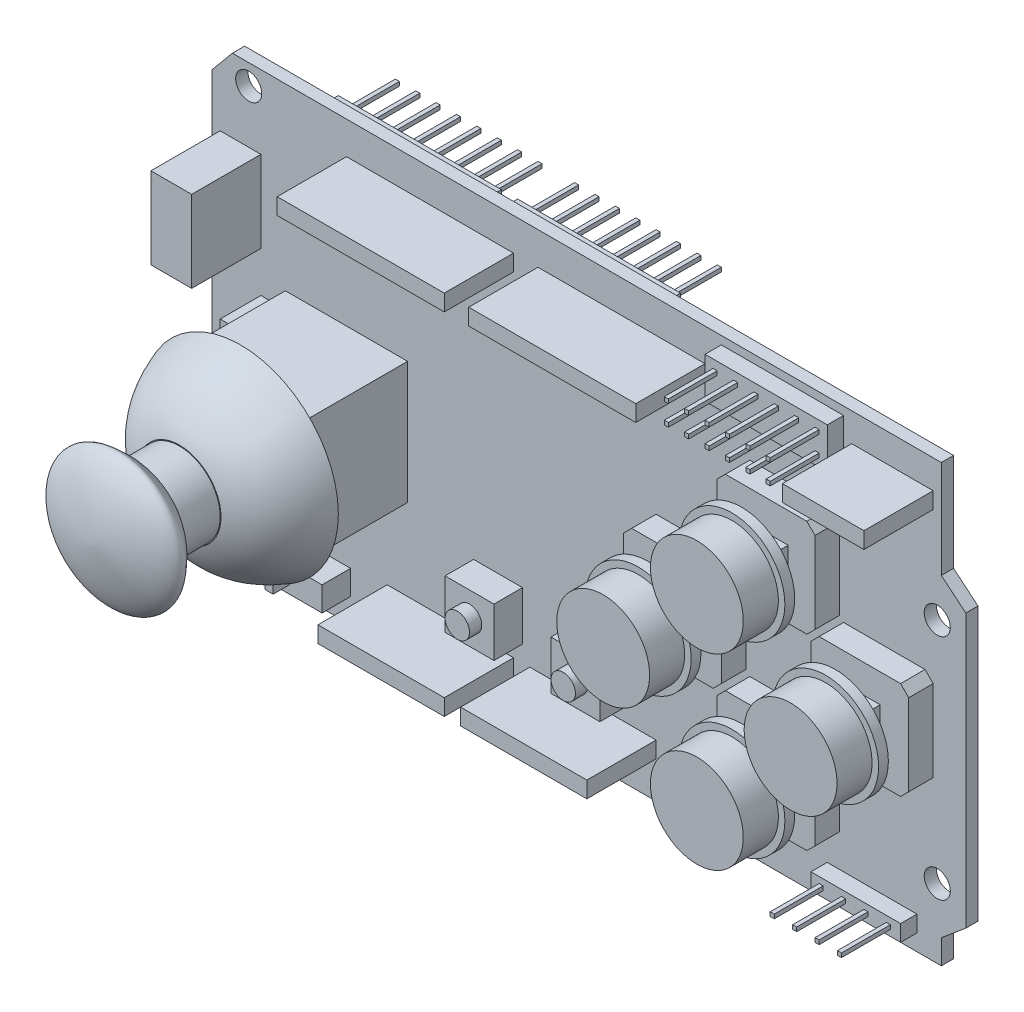
SolidWorks part; units mm, degrees
ref_plane "前视基准面" through (0, 0, 0) normal (0, 0, 1) x (1, 0, 0)
ref_plane "上视基准面" through (0, 0, 0) normal (0, 1, 0) x (1, 0, 0)
ref_plane "右视基准面" through (0, 0, 0) normal (1, 0, 0) x (0, 0, -1)
sketch "草图2" plane through (0, 0, 0) normal (0, 0, 1) x (1, 0, 0)
  line L0 (0, 0) -> (86, 0)
  line L1 (86, 0) -> (86, 3)
  line L2 (86, 3) -> (89, 5.5)
  line L3 (89, 5.5) -> (89, 39)
  line L4 (89, 39) -> (86, 41.5)
  line L5 (86, 41.5) -> (86, 53.5)
  line L6 (0, 0) -> (0, 14)
  line L7 (0, 14) -> (-3.5, 17.5)
  line L8 (-3.5, 17.5) -> (-3.5, 50.5)
  line L9 (-3.5, 50.5) -> (-1, 53.5)
  line L10 (-1, 53.5) -> (86, 53.5)
  dimension "D1" = 86
  dimension "D2" = 3
  dimension "D3" = 2.5
  dimension "D4" = 3
  dimension "D5" = 33.5
  dimension "D6" = 3
  dimension "D7" = 2.5
  dimension "D8" = 53.5
  dimension "D9" = 14
  dimension "D10" = 3.5
  dimension "D11" = 3.5
  dimension "D12" = 33
  dimension "D13" = 2.5
extrude "凸台-拉伸1" add sketch "草图2" along normal blind 1.5
sketch "草图3" plane through (0, 0, 1.5) normal (0, 0, 1) x (1, 0, 0)
  line L0 (89, 5.5) -> (89, 39) construction
  line L1 (86, 53.5) -> (-1, 53.5) construction
  line L2 (-3.5, 50.5) -> (-3.5, 17.5) construction
  circle A0 centre (85.5, 36.5) radius 1.6
  circle A1 centre (85.5, 8.5) radius 1.6
  circle A2 centre (1, 51) radius 1.6
  dimension "D1" = 3.5
  dimension "D2" = 2.5
  dimension "D3" = 28
  dimension "D4" = 2.5
  dimension "D5" = 4.5
extrude "切除-拉伸1" cut sketch "草图3" against normal through all
sketch "草图4" plane through (0, 0, 1.5) normal (0, 0, 1) x (1, 0, 0)
  line L0 (89, 5.5) -> (89, 39) construction
  line L1 (73, 30.5) -> (85, 30.5)
  line L2 (73, 30.5) -> (73, 18.5)
  line L3 (73, 18.5) -> (85, 18.5)
  line L4 (85, 30.5) -> (85, 18.5)
  line L5 (73, 30.5) -> (85, 18.5) construction
  line L6 (73, 18.5) -> (85, 30.5) construction
  circle A0 centre (85.5, 36.5) radius 1.6 construction
  point P0 (79, 24.5)
  dimension "D1" = 12
  dimension "D2" = 12
  dimension "D3" = 4
  dimension "D4" = 6
extrude "凸台-拉伸2" add sketch "草图4" along normal blind 3
chamfer "倒角1" distance 1 angle 45 4 edges at (73, 30.5, 3) (73, 18.5, 3) (85, 18.5, 3) (85, 30.5, 3)
sketch "草图5" plane through (0, 0, 1.5) normal (0, 0, 1) x (1, 0, 0)
  line L0 (84, 30.5) -> (74, 30.5) construction
  line L1 (73, 29.5) -> (73, 19.5) construction
  line L2 (74, 18.5) -> (84, 18.5) construction
  point P0 (67.5, 36)
  point P5 (67.5, 13)
  point P8 (56, 24.5)
  point P11 (79, 24.5)
  dimension "D1" = 5.5
  dimension "D2" = 5.5
  dimension "D3" = 5.5
  dimension "D4" = 11.5
ref_plane "基准面4" through (67.5, 0, 0) normal (-1, 0, 0) x (0, 0, 1)
mirror "镜向1" about plane through (67.5, 0, 0) normal (-1, 0, 0) of "倒角1", "凸台-拉伸2"
sketch "草图6" plane through (0, 0, 1.5) normal (0, 0, 1) x (1, 0, 0)
  line L0 (72.5, 42) -> (73.5, 41)
  line L1 (72.5, 42) -> (62.5, 42)
  line L2 (73.5, 41) -> (73.5, 31)
  line L3 (72.5, 30) -> (62.5, 30)
  line L4 (61.5, 41) -> (61.5, 31)
  line L5 (73.5, 42) -> (61.5, 30) construction
  line L6 (73.5, 30) -> (61.5, 42) construction
  line L7 (72.5, 19) -> (62.5, 19)
  line L8 (73.5, 18) -> (73.5, 8)
  line L9 (72.5, 7) -> (62.5, 7)
  line L10 (61.5, 18) -> (61.5, 8)
  line L11 (73.5, 19) -> (61.5, 7) construction
  line L12 (73.5, 7) -> (61.5, 19) construction
  line L13 (73.5, 31) -> (72.5, 30)
  line L14 (62.5, 42) -> (61.5, 41)
  line L15 (62.5, 30) -> (61.5, 31)
  line L16 (73.5, 18) -> (72.5, 19)
  line L17 (73.5, 8) -> (72.5, 7)
  line L18 (62.5, 19) -> (61.5, 18)
  line L19 (62.5, 7) -> (61.5, 8)
  point P0 (67.5, 36)
  point P6 (67.5, 13)
  dimension "D1" = 12
  dimension "D2" = 12
  dimension "D3" = 12
  dimension "D4" = 12
extrude "凸台-拉伸4" add sketch "草图6" along normal blind 3
sketch "草图7" plane through (0, 0, 4.5) normal (0, 0, 1) x (1, 0, 0)
  line L0 (70.2067, 38.3082) -> (65.2067, 38.3082)
  line L1 (81.5, 27) -> (76.5, 27)
  line L2 (81.5, 27) -> (81.5, 22)
  line L3 (81.5, 22) -> (76.5, 22)
  line L4 (76.5, 27) -> (76.5, 22)
  line L5 (81.5, 27) -> (76.5, 22) construction
  line L6 (81.5, 22) -> (76.5, 27) construction
  line L7 (70.2067, 38.3082) -> (70.2067, 33.3082)
  line L8 (70.2067, 33.3082) -> (65.2067, 33.3082)
  line L9 (65.2067, 38.3082) -> (65.2067, 33.3082)
  line L10 (70.2067, 38.3082) -> (65.2067, 33.3082) construction
  line L11 (70.2067, 33.3082) -> (65.2067, 38.3082) construction
  line L12 (58.565, 27.0711) -> (53.565, 27.0711)
  line L13 (58.565, 27.0711) -> (58.565, 22.0711)
  line L14 (58.565, 22.0711) -> (53.565, 22.0711)
  line L15 (53.565, 27.0711) -> (53.565, 22.0711)
  line L16 (58.565, 27.0711) -> (53.565, 22.0711) construction
  line L17 (58.565, 22.0711) -> (53.565, 27.0711) construction
  line L18 (69.8471, 15.3845) -> (64.8471, 15.3845)
  line L19 (69.8471, 15.3845) -> (69.8471, 10.3845)
  line L20 (69.8471, 10.3845) -> (64.8471, 10.3845)
  line L21 (64.8471, 15.3845) -> (64.8471, 10.3845)
  line L22 (69.8471, 15.3845) -> (64.8471, 10.3845) construction
  line L23 (69.8471, 10.3845) -> (64.8471, 15.3845) construction
  point P0 (79, 24.5)
  point P6 (67.7067, 35.8082)
  point P11 (56.065, 24.5711)
  point P16 (67.3471, 12.8845)
  dimension "D1" = 5
  dimension "D2" = 5
  dimension "D3" = 5
  dimension "D4" = 5
  dimension "D5" = 5
  dimension "D6" = 5
  dimension "D7" = 5
  dimension "D8" = 5
extrude "凸台-拉伸5" add sketch "草图7" along normal blind 3
sketch "草图8" plane through (0, 0, 7.5) normal (0, 0, 1) x (1, 0, 0)
  circle A0 centre (67.5, 36) radius 6.5
  circle A1 centre (67.5, 13) radius 6.5
extrude "凸台-拉伸6" add sketch "草图8" along normal blind 1.2
sketch "草图9" plane through (0, 0, 8.7) normal (0, 0, 1) x (1, 0, 0)
  circle A0 centre (67.5, 36) radius 5.7
  circle A1 centre (67.5, 13) radius 5.7
extrude "凸台-拉伸7" add sketch "草图9" along normal blind 4.3
sketch "草图10" plane through (0, 0, 7.5) normal (0, 0, 1) x (1, 0, 0)
  circle A0 centre (56, 24.5) radius 6.5
  circle A1 centre (79, 24.5) radius 6.5
extrude "凸台-拉伸8" add sketch "草图10" along normal blind 1.2
sketch "草图11" plane through (0, 0, 8.7) normal (0, 0, 1) x (1, 0, 0)
  circle A0 centre (56, 24.5) radius 5.7
  circle A1 centre (79, 24.5) radius 5.7
extrude "凸台-拉伸9" add sketch "草图11" along normal blind 4.3
sketch "草图12" plane through (0, 0, 1.5) normal (0, 0, 1) x (1, 0, 0)
  line L0 (0, 0) -> (86, 0) construction
  line L2 (0, 29) -> (1.5, 29)
  line L3 (0, 29) -> (0, 19)
  line L4 (0, 19) -> (1.5, 19)
  line L6 (1.5, 29) -> (1.5436, 29)
  line L7 (1.5, 19) -> (1.5436, 19)
  line L8 (-3.5, 50.5) -> (-3.5, 17.5) construction
  arc A0 (1.5436, 19) -> (1.5436, 29) centre (13, 24) ccw
  point P9 (0, 24)
  dimension "D1" = 24
  dimension "D4" = 13
  dimension "D2" = 10
  dimension "D3" = 1.5
  dimension "D5" = 0
  dimension "D6" = 3.5
sketch "草图13" plane through (0, 0, 1.5) normal (0, 0, 1) x (1, 0, 0)
  line L0 (5.5, 29.5) -> (2.5, 29.5)
  line L1 (5.5, 16.5) -> (20.5, 16.5)
  line L2 (5.5, 16.5) -> (5.5, 18.5)
  line L3 (5.5, 31.5) -> (20.5, 31.5)
  line L4 (20.5, 16.5) -> (20.5, 31.5)
  line L5 (5.5, 29.5) -> (5.5, 31.5)
  line L10 (2.5, 18.5) -> (2.5, 29.5)
  line L12 (5.5, 18.5) -> (2.5, 18.5)
  point P0 (13, 24)
  point P6 (5.5, 24)
  dimension "D1" = 15
  dimension "D2" = 15
  dimension "D3" = 11
extrude "凸台-拉伸10" add sketch "草图13" along normal blind 13
sketch "草图15" plane through (0, 0, 14.5) normal (0, 0, 1) x (1, 0, 0)
  circle A0 centre (13, 24) radius 12
ref_plane "基准面5" through (0, 0, 22) normal (0, 0, 1) x (1, 0, 0)
sketch "草图16" plane through (0, 0, 22) normal (0, 0, 1) x (1, 0, 0)
  circle A0 centre (13, 24) radius 5.1
ref_plane "基准面6" through (0, 24, 0) normal (0, -1, 0) x (-1, 0, 0)
sketch "草图17" plane through (0, 24, 0) normal (0, -1, 0) x (-1, 0, 0)
  line L8 (-18.1, -22) -> (-7.9, -22) construction
  line L9 (-8.25, -22) -> (8.25, -22) construction
  line L10 (-25, -14.5) -> (-1, -14.5) construction
  line L11 (-18.1, -22) -> (-13, -22)
  line L12 (-13, -22) -> (-13, -14.5)
  line L13 (-13, -14.5) -> (-25, -14.5)
  spline S0 degree 2 poles (-18.1, -22) (-23.0643, -20.3891) (-25, -14.5) knots 0 0 0 1 1 1
extrude "凸台-拉伸11" add sketch "草图16" against normal blind 13 contours A0
revolve "旋转1" add sketch "草图17" angle 360 about L12
sketch "草图18" plane through (0, 18.5, 0) normal (0, -1, 0) x (1, 0, 0)
  line L0 (5.5, 14.5) -> (5.5, 1.5) construction
  line L1 (2.5, 14.5) -> (5.5, 14.5)
  line L2 (2.5, 14.5) -> (2.5, 6.5)
  line L3 (2.5, 6.5) -> (5.5, 6.5)
  line L4 (5.5, 14.5) -> (5.5, 6.5)
  dimension "D1" = 8
extrude "切除-拉伸2" cut sketch "草图18" against normal through all
sketch "草图19" plane through (0, 0, 22) normal (0, 0, 1) x (1, 0, 0)
  circle A0 centre (13, 24) radius 5
extrude "凸台-拉伸12" add sketch "草图19" along normal blind 5
sketch "草图20" plane through (0, 24, 0) normal (0, -1, 0) x (-1, 0, 0)
  line L0 (-13, -27) -> (-13, -33)
  line L1 (-18, -27) -> (-8, -27) construction
  line L2 (-18, -27) -> (-13, -27)
  spline S0 degree 3 poles (-13, -33) (-17.4258, -32.7506) (-22.378, -30.5813) (-20.7084, -28.8669) (-19.1499, -27.0475) (-18, -27) knots 0 0 0 0 0.726319 0.826319 1 1 1 1
  dimension "D1" = 6
revolve "旋转2" add sketch "草图20" angle 360 about L0
sketch "草图21" plane through (0, 0, 1.5) normal (0, 0, 1) x (1, 0, 0)
  line L0 (86, 41.5) -> (86, 53.5) construction
  line L1 (59, 52.5) -> (74, 52.5)
  line L2 (59, 52.5) -> (59, 47.5)
  line L3 (59, 47.5) -> (74, 47.5)
  line L4 (74, 52.5) -> (74, 47.5)
  line L5 (86, 53.5) -> (-1, 53.5) construction
  dimension "D1" = 15
  dimension "D2" = 5
  dimension "D3" = 12
  dimension "D4" = 1
extrude "凸台-拉伸13" add sketch "草图21" along normal blind 2
sketch "草图22" plane through (0, 0, 1.5) normal (0, 0, 1) x (1, 0, 0)
  line L0 (0, 0) -> (86, 0) construction
  line L1 (72, 2) -> (83, 2)
  line L2 (72, 2) -> (72, 4)
  line L3 (72, 4) -> (83, 4)
  line L4 (83, 2) -> (83, 4)
  line L5 (86, 0) -> (86, 3) construction
  dimension "D1" = 11
  dimension "D2" = 2
  dimension "D3" = 2
  dimension "D4" = 3
extrude "凸台-拉伸14" add sketch "草图22" along normal blind 2
sketch "草图23" plane through (0, 0, 3.5) normal (0, 0, 1) x (1, 0, 0)
  line L0 (72, 4) -> (72, 2) construction
  line L1 (73, 2.75) -> (73.5, 2.75)
  line L2 (73, 2.75) -> (73, 3.25)
  line L3 (73, 3.25) -> (73.5, 3.25)
  line L4 (73.5, 2.75) -> (73.5, 3.25)
  line L5 (83, 4) -> (72, 4) construction
  dimension "D1" = 0.5
  dimension "D2" = 0.5
  dimension "D3" = 1
  dimension "D4" = 0.75
extrude "凸台-拉伸15" add sketch "草图23" along normal blind 6
pattern_linear "阵列(线性)1" count 4 spacing 2.75 along (1, 0, 0) of "凸台-拉伸15"
sketch "草图24" plane through (0, 0, 3.5) normal (0, 0, 1) x (1, 0, 0)
  line L0 (59, 47.5) -> (74, 47.5) construction
  line L1 (73, 48.5) -> (72.5, 48.5)
  line L2 (73, 48.5) -> (73, 49)
  line L3 (73, 49) -> (72.5, 49)
  line L4 (72.5, 48.5) -> (72.5, 49)
  line L5 (74, 47.5) -> (74, 52.5) construction
  line L6 (74, 52.5) -> (59, 52.5) construction
  line L7 (73, 51) -> (72.5, 51)
  line L8 (73, 51) -> (73, 51.5)
  line L9 (73, 51.5) -> (72.5, 51.5)
  line L10 (72.5, 51) -> (72.5, 51.5)
  dimension "D1" = 0.5
  dimension "D2" = 0.5
  dimension "D3" = 1
  dimension "D4" = 1
  dimension "D5" = 0.5
  dimension "D6" = 1
extrude "凸台-拉伸16" add sketch "草图24" along normal blind 6
pattern_linear "阵列(线性)2" count 6 spacing 2.5 along (-1, 0, 0) of "凸台-拉伸16"
sketch "草图25" plane through (0, 0, 1.5) normal (0, 0, 1) x (1, 0, 0)
  line L0 (86, 53.5) -> (-1, 53.5) construction
  line L1 (85, 48) -> (75, 48)
  line L2 (85, 48) -> (85, 50)
  line L3 (85, 50) -> (75, 50)
  line L4 (75, 48) -> (75, 50)
  line L5 (74, 47.5) -> (74, 52.5) construction
  line L6 (59, 52.5) -> (59, 47.5) construction
  line L7 (57, 47.5) -> (36.5, 47.5)
  line L8 (57, 47.5) -> (57, 49.5)
  line L9 (57, 49.5) -> (36.5, 49.5)
  line L10 (36.5, 47.5) -> (36.5, 49.5)
  line L11 (33.5, 47.5) -> (13, 47.5)
  line L12 (33.5, 47.5) -> (33.5, 49.5)
  line L13 (33.5, 49.5) -> (13, 49.5)
  line L14 (13, 47.5) -> (13, 49.5)
  line L15 (-3.5, 50.5) -> (-3.5, 17.5) construction
  line L16 (2.5, 34.5) -> (-2.5, 34.5)
  line L17 (2.5, 34.5) -> (2.5, 44.5)
  line L18 (2.5, 44.5) -> (-2.5, 44.5)
  line L19 (-2.5, 34.5) -> (-2.5, 44.5)
  line L20 (0, 14) -> (0, 0) construction
  line L21 (51, 4.5) -> (35.5, 4.5)
  line L22 (51, 4.5) -> (51, 6.5)
  line L23 (51, 6.5) -> (35.5, 6.5)
  line L24 (35.5, 4.5) -> (35.5, 6.5)
  line L25 (33.5, 4.5) -> (18, 4.5)
  line L26 (33.5, 4.5) -> (33.5, 6.5)
  line L27 (33.5, 6.5) -> (18, 6.5)
  line L28 (18, 4.5) -> (18, 6.5)
  line L29 (0, 0) -> (86, 0) construction
  dimension "D1" = 10
  dimension "D2" = 2
  dimension "D3" = 3.5
  dimension "D4" = 1
  dimension "D5" = 20.5
  dimension "D6" = 20.5
  dimension "D7" = 2
  dimension "D8" = 2
  dimension "D9" = 2
  dimension "D10" = 4
  dimension "D11" = 3
  dimension "D12" = 4
  dimension "D13" = 10
  dimension "D14" = 5
  dimension "D15" = 1
  dimension "D16" = 9
  dimension "D17" = 15.5
  dimension "D18" = 15.5
  dimension "D19" = 2
  dimension "D20" = 2
  dimension "D21" = 18
  dimension "D22" = 4.5
  dimension "D23" = 4.5
  dimension "D24" = 2
extrude "凸台-拉伸17" add sketch "草图25" along normal blind 8.5
sketch "草图26" plane through (0, 0, 1.5) normal (0, 0, 1) x (1, 0, 0)
  line L0 (0, 14) -> (0, 0) construction
  line L1 (4.5, 6) -> (13.5, 6)
  line L2 (4.5, 6) -> (4.5, 3)
  line L3 (4.5, 3) -> (13.5, 3)
  line L4 (13.5, 6) -> (13.5, 3)
  line L5 (0, 0) -> (86, 0) construction
  dimension "D1" = 9
  dimension "D2" = 3
  dimension "D3" = 4.5
  dimension "D4" = 3
extrude "凸台-拉伸18" add sketch "草图26" along normal blind 3.5
sketch "草图27" plane through (0, 0, 5) normal (0, 0, 1) x (1, 0, 0)
  line L0 (4.5, 3) -> (13.5, 3) construction
  line L1 (8.5, 5) -> (9.5, 5)
  line L2 (8.5, 5) -> (8.5, 4)
  line L3 (8.5, 4) -> (9.5, 4)
  line L4 (9.5, 5) -> (9.5, 4)
  line L5 (4.5, 6) -> (4.5, 3) construction
  dimension "D1" = 1
  dimension "D2" = 1
  dimension "D3" = 1
  dimension "D4" = 4
extrude "凸台-拉伸19" add sketch "草图27" along normal blind 2
sketch "草图28" plane through (0, 0, 1.5) normal (0, 0, 1) x (1, 0, 0)
  line L0 (33.5, 4.5) -> (33.5, 6.5) construction
  line L1 (28.6, 14.5) -> (34.6, 14.5)
  line L2 (28.6, 14.5) -> (28.6, 8.5)
  line L3 (28.6, 8.5) -> (34.6, 8.5)
  line L4 (34.6, 14.5) -> (34.6, 8.5)
  line L5 (41.6, 14.5) -> (47.6, 14.5)
  line L6 (41.6, 14.5) -> (41.6, 8.5)
  line L7 (41.6, 8.5) -> (47.6, 8.5)
  line L8 (47.6, 14.5) -> (47.6, 8.5)
  line L9 (33.5, 6.5) -> (18, 6.5) construction
  line L10 (51, 6.5) -> (35.5, 6.5) construction
  point P10 (33.5, 5.5)
  dimension "D1" = 6
  dimension "D2" = 6
  dimension "D3" = 6
  dimension "D4" = 6
  dimension "D5" = 1.1
  dimension "D6" = 2
  dimension "D7" = 2
  dimension "D8" = 7
extrude "凸台-拉伸20" add sketch "草图28" along normal blind 3.5
sketch "草图29" plane through (0, 0, 5) normal (0, 0, 1) x (1, 0, 0)
  circle A0 centre (31.6, 11.5) radius 1.5
  circle A1 centre (44.6, 11.5) radius 1.5
extrude "凸台-拉伸21" add sketch "草图29" along normal blind 1.5
sketch "草图30" plane through (0, 0, 0) normal (0, 0, -1) x (-1, 0, 0)
  line L0 (0, 14) -> (0, 0) construction
  line L1 (-18, 2) -> (-33, 2)
  line L2 (-18, 2) -> (-18, 4)
  line L3 (-18, 4) -> (-33, 4)
  line L4 (-33, 2) -> (-33, 4)
  line L5 (-36, 2) -> (-51, 2)
  line L6 (-36, 2) -> (-36, 4)
  line L7 (-36, 4) -> (-51, 4)
  line L8 (-51, 2) -> (-51, 4)
  line L9 (0, 0) -> (-86, 0) construction
  line L10 (3.5, 50.5) -> (3.5, 17.5) construction
  line L11 (-8.5, 50) -> (-28.5, 50)
  line L12 (-8.5, 50) -> (-8.5, 52)
  line L13 (-8.5, 52) -> (-28.5, 52)
  line L14 (-28.5, 50) -> (-28.5, 52)
  line L15 (-30.5, 50) -> (-50.5, 50)
  line L16 (-30.5, 50) -> (-30.5, 52)
  line L17 (-30.5, 52) -> (-50.5, 52)
  line L18 (-50.5, 50) -> (-50.5, 52)
  line L19 (-86, 53.5) -> (1, 53.5) construction
  dimension "D1" = 15
  dimension "D2" = 15
  dimension "D3" = 2
  dimension "D4" = 2
  dimension "D5" = 18
  dimension "D6" = 2
  dimension "D7" = 2
  dimension "D8" = 3
  dimension "D9" = 20
  dimension "D10" = 20
  dimension "D11" = 2
  dimension "D12" = 2
  dimension "D13" = 2
  dimension "D14" = 12
  dimension "D15" = 1.5
extrude "凸台-拉伸22" add sketch "草图30" along normal blind 2
sketch "草图31" plane through (0, 0, -2) normal (0, 0, -1) x (-1, 0, 0)
  line L0 (-33, 2) -> (-18, 2) construction
  line L1 (-19, 2.75) -> (-19.5, 2.75)
  line L2 (-19, 2.75) -> (-19, 3.25)
  line L3 (-19, 3.25) -> (-19.5, 3.25)
  line L4 (-19.5, 2.75) -> (-19.5, 3.25)
  line L5 (-37, 2.75) -> (-37.5, 2.75)
  line L6 (-37, 2.75) -> (-37, 3.25)
  line L7 (-37, 3.25) -> (-37.5, 3.25)
  line L8 (-37.5, 2.75) -> (-37.5, 3.25)
  line L9 (-18, 2) -> (-18, 4) construction
  line L10 (-36, 2) -> (-36, 4) construction
  line L11 (-36, 4) -> (-51, 4) construction
  dimension "D1" = 0.5
  dimension "D2" = 0.5
  dimension "D3" = 0.5
  dimension "D4" = 0.5
  dimension "D5" = 0.75
  dimension "D6" = 1
  dimension "D7" = 1
  dimension "D8" = 0.75
extrude "凸台-拉伸23" add sketch "草图31" along normal blind 6
pattern_linear "阵列(线性)3" count 6 spacing 2.5 along (1, 0, 0) of "凸台-拉伸23"
sketch "草图32" plane through (0, 0, -2) normal (0, 0, -1) x (-1, 0, 0)
  line L0 (-50.5, 50) -> (-30.5, 50) construction
  line L1 (-9.5, 50.75) -> (-10, 50.75)
  line L2 (-9.5, 50.75) -> (-9.5, 51.25)
  line L3 (-9.5, 51.25) -> (-10, 51.25)
  line L4 (-10, 50.75) -> (-10, 51.25)
  line L5 (-31.5, 50.75) -> (-32, 50.75)
  line L6 (-31.5, 50.75) -> (-31.5, 51.25)
  line L7 (-31.5, 51.25) -> (-32, 51.25)
  line L8 (-32, 50.75) -> (-32, 51.25)
  line L9 (-28.5, 50) -> (-8.5, 50) construction
  line L10 (-8.5, 50) -> (-8.5, 52) construction
  line L11 (-30.5, 50) -> (-30.5, 52) construction
  dimension "D1" = 0.5
  dimension "D2" = 0.5
  dimension "D3" = 0.5
  dimension "D4" = 0.5
  dimension "D5" = 0.75
  dimension "D6" = 0.75
  dimension "D7" = 1
  dimension "D8" = 1
extrude "凸台-拉伸24" add sketch "草图32" along normal blind 6
pattern_linear "阵列(线性)4" count 8 spacing 2.5 along (1, 0, 0) of "凸台-拉伸24"
